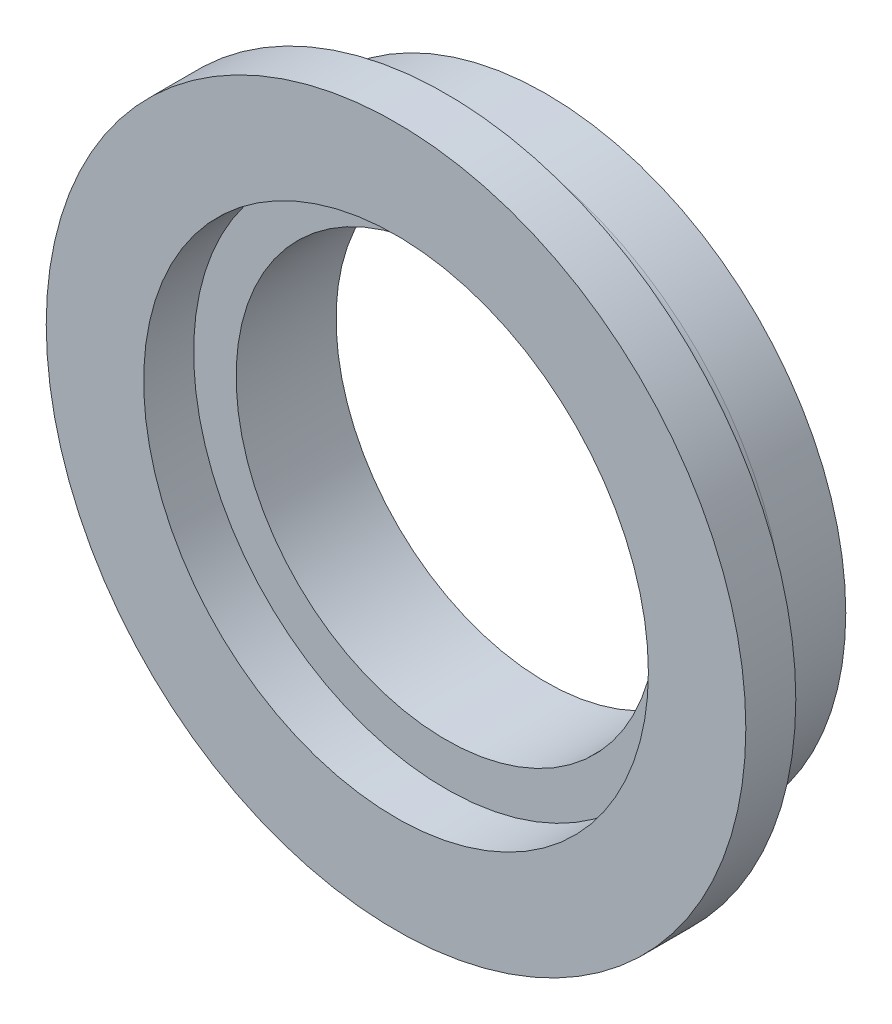
SolidWorks part; units mm, degrees
material "Nylon 101"
ref_plane "Front Plane" through (0, 0, 0) normal (0, 0, 1) x (1, 0, 0)
ref_plane "Top Plane" through (0, 0, 0) normal (0, 1, 0) x (1, 0, 0)
ref_plane "Right Plane" through (0, 0, 0) normal (1, 0, 0) x (0, 0, -1)
sketch "Sketch1" plane through (0, 0, 0) normal (0, 0, 1) x (1, 0, 0)
  circle A0 centre (0, 0) radius 13.335
  circle A1 centre (0, 0) radius 19.05
  dimension "D1" = 26.67
  dimension "D2" = 38.1
extrude "Boss-Extrude1" add sketch "Sketch1" along normal mid plane 6.35
sketch "Sketch2" plane through (0, 0, 3.175) normal (0, 0, 1) x (1, 0, 0)
  circle A0 centre (0, 0) radius 16.0337
  circle A1 centre (0, 0) radius 22.225
  dimension "D1" = 44.45
  dimension "D2" = 32.0675
extrude "Boss-Extrude2" add sketch "Sketch2" along normal blind 3.175
fillet "Fillet1" radius 2.54 1 edges at (19.05, 0, 3.175)
